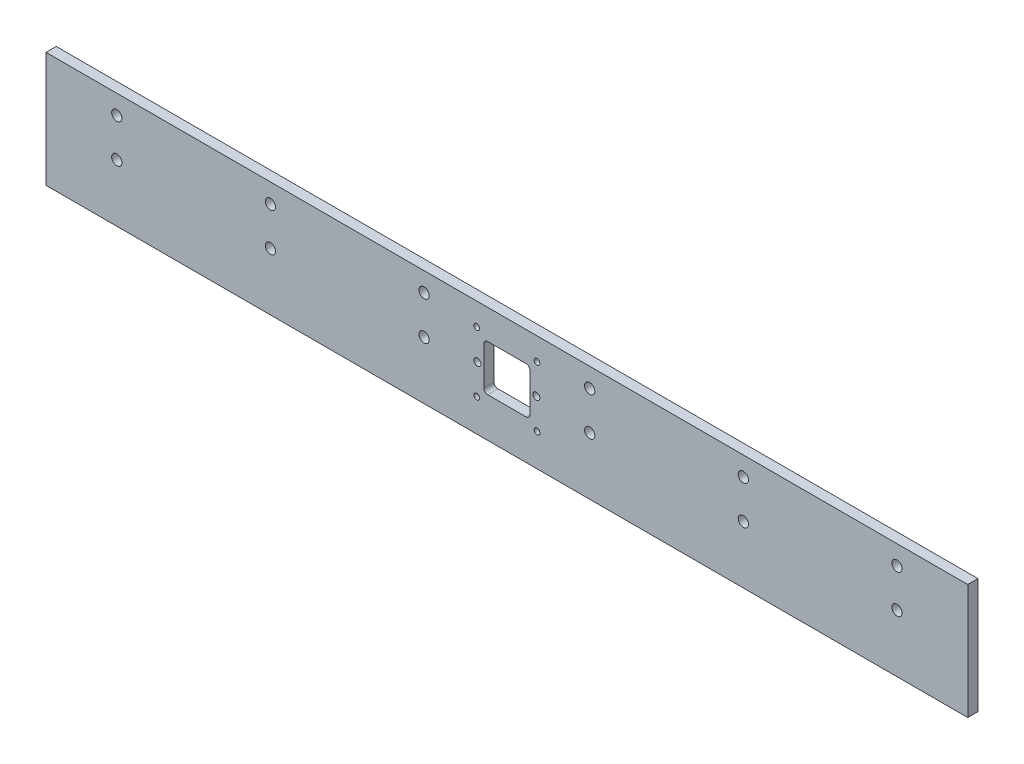
SolidWorks part; units mm, degrees
material "1023 Tôle d'acier non allié (SS)"
ref_plane "Plan de face" through (0, 0, 0) normal (0, 0, 1) x (1, 0, 0)
ref_plane "Plan de dessus" through (0, 0, 0) normal (0, 1, 0) x (1, 0, 0)
ref_plane "Plan de droite" through (0, 0, 0) normal (1, 0, 0) x (0, 0, -1)
sketch "Esquisse1" plane through (0, 0, 0) normal (0, 0, 1) x (1, 0, 0)
  line L0 (317, 48.92) -> (363, 48.92) construction
  line L1 (0, 0) -> (680, 0)
  line L2 (0, 0) -> (0, 90)
  line L3 (0, 90) -> (680, 90)
  line L4 (680, 0) -> (680, 90)
  line L5 (340, 48.92) -> (340, 30.92) construction
  line L6 (340, 30.92) -> (355, 30.92)
  line L7 (358, 33.92) -> (358, 63.92)
  line L8 (355, 66.92) -> (325, 66.92)
  line L9 (322, 63.92) -> (322, 33.92)
  line L10 (325, 30.92) -> (340, 30.92)
  line L11 (325, 63.92) -> (355, 33.92) construction
  line L12 (325, 33.92) -> (355, 63.92) construction
  line L13 (35.3, 75) -> (340, 75) construction
  circle A0 centre (317, 48.92) radius 2.75
  circle A1 centre (363, 48.92) radius 2.75
  circle A2 centre (316.45, 72.47) radius 2.25
  circle A3 centre (363.55, 72.47) radius 2.25
  arc A4 (325, 30.92) -> (322, 33.92) centre (325, 33.92) cw
  arc A5 (322, 63.92) -> (325, 66.92) centre (325, 63.92) cw
  arc A6 (355, 66.92) -> (358, 63.92) centre (355, 63.92) cw
  arc A7 (358, 33.92) -> (355, 30.92) centre (355, 33.92) cw
  circle A8 centre (363.55, 25.37) radius 2.25
  circle A9 centre (316.45, 25.37) radius 2.25
  circle A10 centre (35.3, 75) radius 4
  circle A11 centre (35.3, 45) radius 4
  circle A12 centre (644.7, 45) radius 4
  circle A13 centre (644.7, 75) radius 4
  circle A14 centre (155.3, 75) radius 4
  circle A15 centre (155.3, 45) radius 4
  circle A16 centre (275.3, 75) radius 4
  circle A17 centre (275.3, 45) radius 4
  circle A18 centre (404.7, 45) radius 4
  circle A19 centre (404.7, 75) radius 4
  circle A20 centre (524.7, 75) radius 4
  circle A21 centre (524.7, 45) radius 4
  point P21 (322, 30.92)
  point P24 (322, 66.92)
  point P27 (358, 66.92)
  point P30 (358, 30.92)
  dimension "D4" = 5.5
  dimension "D12" = 3
  dimension "D15" = 4.5
  dimension "D16" = 47.1
  dimension "D14" = 4.5
  dimension "D19" = 8
  dimension "D20" = 8
  dimension "D21" = 15
  dimension "D22" = 35.3
  dimension "D23" = 35.3
  dimension "D24" = 30
  dimension "D1" = 680
  dimension "D2" = 90
  dimension "D3" = 317
  dimension "D5" = 41.08
  dimension "D8" = 18
  dimension "D9" = 36
  dimension "D10" = 36
  dimension "D11" = 36
  dimension "D13" = 18
  dimension "D17" = 23.55
  dimension "D18" = 23
  dimension "D6" = 2
  dimension "D7" = 1
  dimension "D25" = 3
extrude "Boss.-Extru.1" add sketch "Esquisse1" along normal blind 8
sketch "Esquisse2" plane through (680, 0, 0) normal (1, 0, 0) x (0, 0, -1)
  line L1 (-8, 90) -> (0, 90)
  line L2 (-8, 90) -> (-8, 0)
  line L3 (-8, 0) -> (0, 0)
  line L4 (0, 90) -> (0, 0)
extrude "Boss.-Extru.2" add sketch "Esquisse2" along normal blind 20
sketch "Esquisse3" plane through (0, 0, 0) normal (-1, 0, 0) x (0, 0, 1)
  line L1 (0, 90) -> (8, 90)
  line L2 (0, 90) -> (0, 0)
  line L3 (0, 0) -> (8, 0)
  line L4 (8, 90) -> (8, 0)
extrude "Boss.-Extru.3" add sketch "Esquisse3" along normal blind 20
